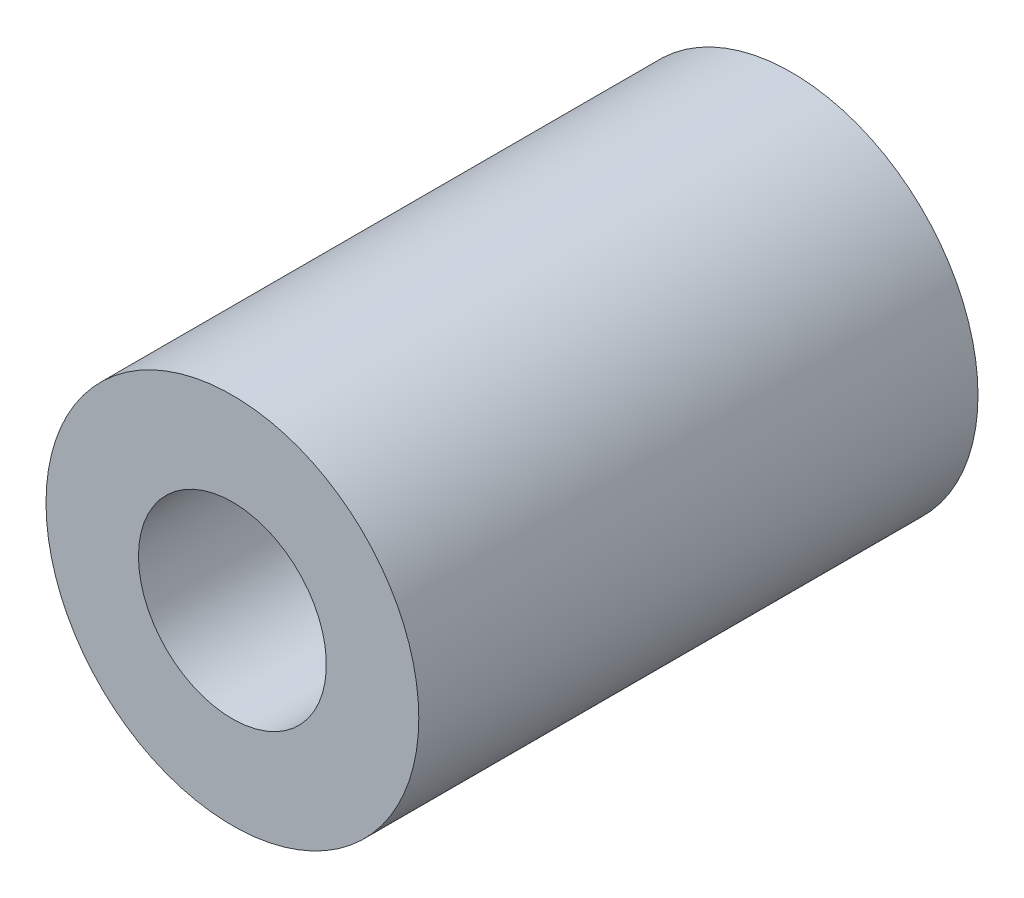
SolidWorks part; units mm, degrees
ref_plane "Front Plane" through (0, 0, 0) normal (0, 0, 1) x (1, 0, 0)
ref_plane "Top Plane" through (0, 0, 0) normal (0, 1, 0) x (1, 0, 0)
ref_plane "Right Plane" through (0, 0, 0) normal (1, 0, 0) x (0, 0, -1)
sketch "Sketch1" plane through (0, 0, 0) normal (0, 0, 1) x (1, 0, 0)
  circle A0 centre (0, 0) radius 6.35
  circle A1 centre (0, 0) radius 3.2004
  dimension "OD" = 12.7
  dimension "ID" = 6.4008
extrude "Extrude1" add sketch "Sketch1" along normal mid plane 19.05
sketch "Sketch2" plane through (0, 0, 0) normal (1, 0, 0) x (0, 0, -1)
  line L0 (-9.525, -3.2004) -> (9.525, -3.2004) construction
  line L3 (9.525, 3.2004) -> (-9.525, 3.2004) construction
  line L5 (-9.525, -3.2004) -> (9.525, -3.2004)
  line L6 (9.525, 3.2004) -> (-9.525, 3.2004)
sketch "Sketch4" plane through (0, 0, 9.525) normal (0, 0, 1) x (1, 0, 0)
  line L0 (0, 0) -> (-2.263, 2.263)
  line L1 (0, -55) -> (0, 55) construction
  circle A0 centre (0, 0) radius 3.2004 construction
  dimension "D1" = 45
